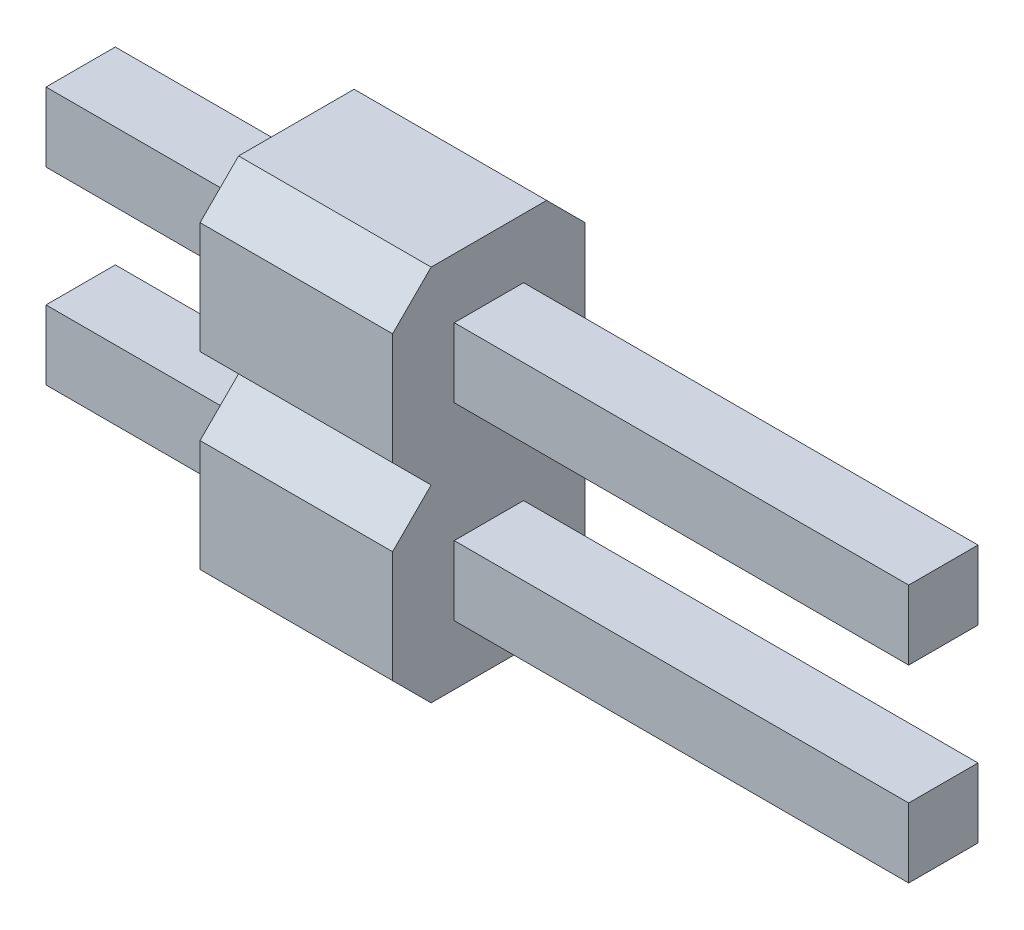
SolidWorks part; units mm, degrees
ref_plane "Přední rovina" through (0, 0, 0) normal (0, 0, 1) x (1, 0, 0)
ref_plane "Horní rovina" through (0, 0, 0) normal (0, 1, 0) x (1, 0, 0)
ref_plane "Pravá rovina" through (0, 0, 0) normal (1, 0, 0) x (0, 0, -1)
sketch "Skica1" plane through (0, 0, 0) normal (0, 0, 1) x (1, 0, 0)
  line L0 (0, 0) -> (-2.2149, 0) construction
  line L2 (0, 0) -> (-2.5, 0)
  line L3 (0, 0) -> (0, 4.9)
  line L4 (0, 4.9) -> (-2.5, 4.9)
  line L5 (-2.5, 0) -> (-2.5, 4.9)
  dimension "D1" = 2.5
  dimension "D2" = 4.9
extrude "Přidat vysunutím1" add sketch "Skica1" along normal blind 2.5
sketch "Skica3" plane through (0, 0, 0) normal (1, 0, 0) x (0, 0, -1)
  line L0 (-2.5, 2.45) -> (0, 2.45) construction
  line L1 (-2.5, 0) -> (-2.5, 4.9) construction
  line L2 (0, 0) -> (0, 4.9) construction
  line L3 (-2.5, 2.95) -> (-2, 2.45)
  line L4 (-2, 2.45) -> (-2.5, 1.95)
  line L5 (-2.5, 1.95) -> (-2.5, 2.95)
  line L6 (0, 2.95) -> (-0.5, 2.45)
  line L7 (-0.5, 2.45) -> (0, 1.95)
  line L8 (0, 1.95) -> (0, 2.95)
  line L9 (-2, 4.9) -> (-2.5, 4.4)
  line L10 (-2.5, 4.9) -> (0, 4.9) construction
  line L11 (-2.5, 4.4) -> (-2.5, 4.9)
  line L12 (-2.5, 4.9) -> (-2, 4.9)
  line L13 (-2.5, 0.5) -> (-2, 0)
  line L14 (-2.5, 0) -> (0, 0) construction
  line L15 (-2, 0) -> (-2.5, 0)
  line L16 (-2.5, 0) -> (-2.5, 0.5)
  line L17 (-0.5, 0) -> (0, 0.5)
  line L18 (0, 0.5) -> (0, 0)
  line L19 (0, 0) -> (-0.5, 0)
  line L20 (0, 4.9) -> (0, 4.4)
  line L21 (0, 4.4) -> (-0.5, 4.9)
  line L22 (-0.5, 4.9) -> (0, 4.9)
  dimension "D1" = 1
  dimension "D2" = 0.5
  dimension "D3" = 0.5
  dimension "D4" = 45
  dimension "D5" = 45
  dimension "D6" = 0.5
  dimension "D7" = 0.5
  dimension "D8" = 45
  dimension "D9" = 45
extrude "Odebrat vysunutím1" cut sketch "Skica3" against normal blind 2.5
sketch "Skica4" plane through (0, 0, 0) normal (1, 0, 0) x (0, 0, -1)
  line L0 (-1.25, 4.9) -> (-1.25, 0) construction
  line L1 (-2, 4.9) -> (-0.5, 4.9) construction
  line L2 (-2, 0) -> (-0.5, 0) construction
  line L3 (-2.5, 3.675) -> (0, 3.675) construction
  line L4 (-2.5, 2.95) -> (-2.5, 4.4) construction
  line L5 (0, 2.95) -> (0, 4.4) construction
  line L6 (-2.5, 1.225) -> (0, 1.225) construction
  line L7 (-2.5, 0.5) -> (-2.5, 1.95) construction
  line L8 (0, 0.5) -> (0, 1.95) construction
  line L10 (-1.7, 4.125) -> (-0.8, 4.125)
  line L11 (-1.7, 4.125) -> (-1.7, 3.225)
  line L12 (-1.7, 3.225) -> (-0.8, 3.225)
  line L13 (-0.8, 4.125) -> (-0.8, 3.225)
  line L14 (-1.7, 4.125) -> (-0.8, 3.225) construction
  line L15 (-1.7, 3.225) -> (-0.8, 4.125) construction
  line L16 (-1.7, 1.675) -> (-0.8, 1.675)
  line L17 (-1.7, 1.675) -> (-1.7, 0.775)
  line L18 (-1.7, 0.775) -> (-0.8, 0.775)
  line L19 (-0.8, 1.675) -> (-0.8, 0.775)
  line L20 (-1.7, 1.675) -> (-0.8, 0.775) construction
  line L21 (-1.7, 0.775) -> (-0.8, 1.675) construction
  point P18 (-1.25, 3.675)
  point P23 (-1.25, 1.225)
  dimension "D1" = 0.9
extrude "Přidat vysunutím2" add sketch "Skica4" along normal blind 5.9
sketch "Skica5" plane through (-2.5, 0, 0) normal (-1, 0, 0) x (0, 0, 1)
  line L0 (0.8, 3.225) -> (0.8, 4.125) construction
  line L1 (0.8, 4.125) -> (1.7, 4.125) construction
  line L2 (1.7, 4.125) -> (1.7, 3.225) construction
  line L3 (1.7, 3.225) -> (0.8, 3.225) construction
  line L4 (0.8, 0.775) -> (0.8, 1.675) construction
  line L5 (0.8, 1.675) -> (1.7, 1.675) construction
  line L6 (1.7, 1.675) -> (1.7, 0.775) construction
  line L7 (1.7, 0.775) -> (0.8, 0.775) construction
  line L8 (0.8, 3.225) -> (0.8, 4.125)
  line L9 (0.8, 4.125) -> (1.7, 4.125)
  line L10 (1.7, 4.125) -> (1.7, 3.225)
  line L11 (1.7, 3.225) -> (0.8, 3.225)
  line L12 (0.8, 0.775) -> (0.8, 1.675)
  line L13 (0.8, 1.675) -> (1.7, 1.675)
  line L14 (1.7, 1.675) -> (1.7, 0.775)
  line L15 (1.7, 0.775) -> (0.8, 0.775)
extrude "Přidat vysunutím3" add sketch "Skica5" along normal blind 2.8
